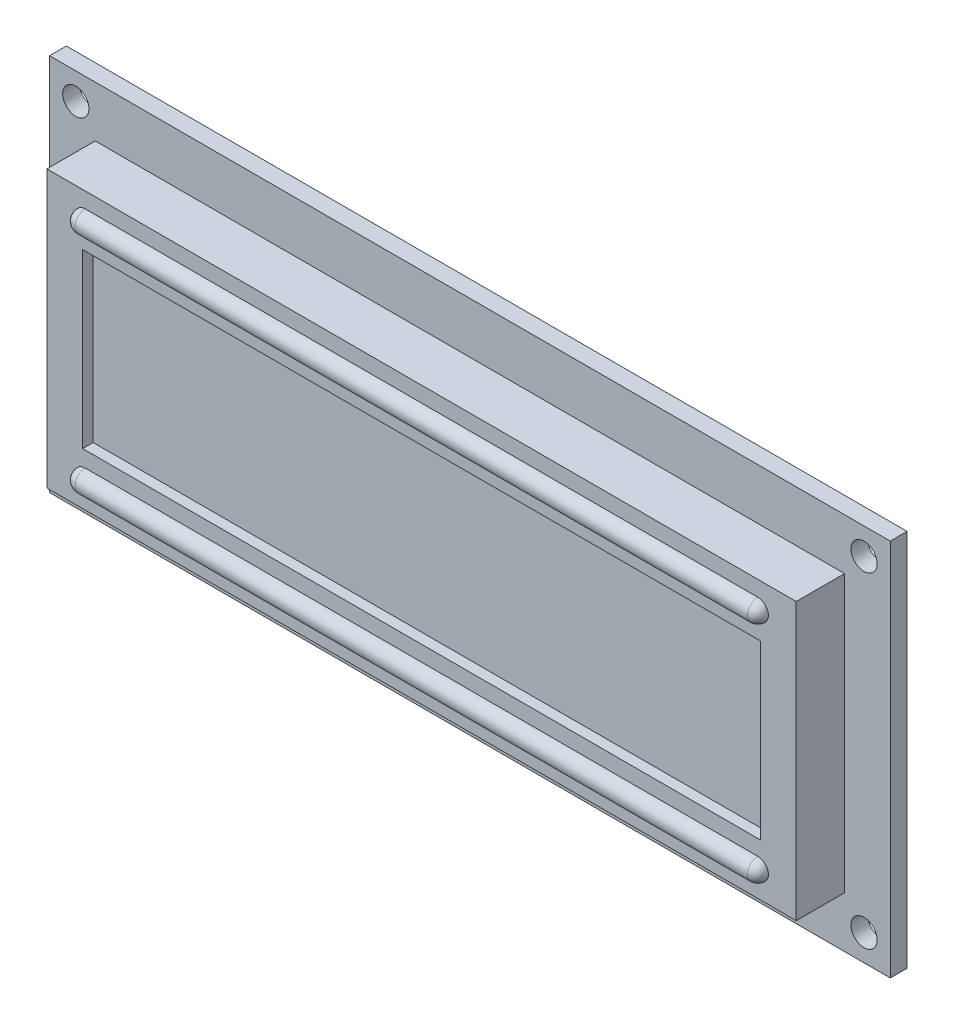
SolidWorks part; units mm, degrees
ref_plane "Alzado" through (0, 0, 0) normal (0, 0, 1) x (1, 0, 0)
ref_plane "Planta" through (0, 0, 0) normal (0, 1, 0) x (1, 0, 0)
ref_plane "Vista lateral" through (0, 0, 0) normal (1, 0, 0) x (0, 0, -1)
sketch "Croquis1" plane through (0, 0, 0) normal (0, 0, 1) x (1, 0, 0)
  line L0 (0, 18) -> (2.5, 18) construction
  line L1 (0, 0) -> (80, 0)
  line L2 (0, 0) -> (0, 36)
  line L3 (0, 36) -> (80, 36)
  line L4 (80, 0) -> (80, 36)
  line L5 (2.5, 18) -> (2.5, 33.5) construction
  line L6 (2.5, 18) -> (2.5, 2.5) construction
  line L7 (2.5, 2.5) -> (77.5, 2.5) construction
  line L8 (77.5, 2.5) -> (77.5, 33.5) construction
  line L9 (77.5, 33.5) -> (2.5, 33.5) construction
  circle A0 centre (77.5, 33.5) radius 1.25
  circle A1 centre (77.5, 2.5) radius 1.25
  circle A2 centre (2.5, 2.5) radius 1.25
  circle A3 centre (2.5, 33.5) radius 1.25
  dimension "D7" = 2.5
  dimension "D8" = 2.5
  dimension "D9" = 2.5
  dimension "D10" = 2.5
  dimension "D1" = 80
  dimension "D2" = 36
  dimension "D3" = 2.5
  dimension "D4" = 15.5
  dimension "D5" = 15.5
  dimension "D6" = 75
extrude "Saliente-Extruir2" add sketch "Croquis1" along normal blind 1.6
sketch "Croquis2" plane through (0, 0, 1.6) normal (0, 0, 1) x (1, 0, 0)
  line L0 (0, 18) -> (4.35, 18) construction
  line L1 (0, 36) -> (0, 0) construction
  line L2 (4.35, 18) -> (4.35, 31.15) construction
  line L3 (80, 0) -> (80, 36) construction
  line L4 (4.35, 31.15) -> (75.65, 31.15)
  line L5 (4.35, 31.15) -> (4.35, 4.85)
  line L6 (4.35, 4.85) -> (75.65, 4.85)
  line L7 (75.65, 31.15) -> (75.65, 4.85)
  line L8 (0, 0) -> (80, 0) construction
  line L9 (80, 36) -> (0, 36) construction
  line L10 (80, 0) -> (80, 36)
  line L11 (0, 0) -> (80, 0)
  line L12 (80, 36) -> (0, 36)
  line L13 (0, 36) -> (0, 0)
  dimension "D1" = 4.35
  dimension "D2" = 13.15
  dimension "D3" = 71.3
  dimension "D4" = 26.3
extrude "Saliente-Extruir3" add sketch "Croquis2" along normal blind 4.6 contours L7 L4 L5 L6
sketch "Croquis3" plane through (0, 0, 6.2) normal (0, 0, 1) x (1, 0, 0)
  line L0 (4.35, 31.15) -> (4.35, 4.85) construction
  line L1 (4.35, 31.15) -> (75.65, 31.15) construction
  line L2 (4.35, 4.85) -> (75.65, 4.85) construction
  line L3 (75.65, 31.15) -> (75.65, 4.85) construction
  line L4 (4.35, 31.15) -> (4.35, 4.85)
  line L5 (4.35, 31.15) -> (75.65, 31.15)
  line L6 (4.35, 4.85) -> (75.65, 4.85)
  line L7 (75.65, 31.15) -> (75.65, 4.85)
  line L8 (4.35, 18) -> (7.75, 18) construction
  line L9 (7.75, 18) -> (7.75, 26.2) construction
  line L11 (7.75, 26.2) -> (72.25, 26.2)
  line L12 (7.75, 26.2) -> (7.75, 9.8)
  line L13 (7.75, 9.8) -> (72.25, 9.8)
  line L14 (72.25, 26.2) -> (72.25, 9.8)
  dimension "D1" = 3.4
  dimension "D2" = 8.2
  dimension "D3" = 64.5
  dimension "D4" = 16.4
extrude "Cortar-Extruir1" cut sketch "Croquis3" against normal blind 1 contours L14 L11 L12 L13
sketch "Croquis4" plane through (0, 0, 6.2) normal (0, 0, 1) x (1, 0, 0)
  line L0 (4.35, 31.15) -> (75.65, 31.15) construction
  line L1 (7.75, 26.2) -> (72.25, 26.2) construction
  line L2 (7.75, 9.8) -> (72.25, 9.8) construction
  line L3 (4.35, 4.85) -> (75.65, 4.85) construction
  line L4 (4.35, 31.15) -> (75.65, 31.15)
  line L5 (7.75, 26.2) -> (72.25, 26.2)
  line L6 (7.75, 9.8) -> (72.25, 9.8)
  line L7 (4.35, 4.85) -> (75.65, 4.85)
  line L8 (40, 31.15) -> (40, 26.2) construction
  line L9 (40, 9.8) -> (40, 4.85) construction
  line L10 (40, 28.675) -> (72, 28.675)
  line L11 (40, 28.675) -> (8, 28.675)
  line L12 (7.75, 18) -> (72.25, 18) construction
  line L13 (7.75, 26.2) -> (7.75, 9.8) construction
  line L14 (72.25, 26.2) -> (72.25, 9.8) construction
  line L15 (40, 7.325) -> (72, 7.325)
  line L16 (40, 7.325) -> (8, 7.325)
  line L17 (72, 29.675) -> (72, 27.675)
  line L18 (72, 8.325) -> (72, 6.325) construction
  line L19 (8, 8.325) -> (8, 6.325) construction
  line L20 (8, 29.675) -> (8, 27.675) construction
  arc A0 (8, 29.675) -> (8, 27.675) centre (8, 28.675) ccw
  arc A1 (72, 27.675) -> (72, 29.675) centre (72, 28.675) ccw
  arc A2 (72, 8.325) -> (72, 6.325) centre (72, 7.325) cw
  arc A3 (8, 6.325) -> (8, 8.325) centre (8, 7.325) cw
  dimension "D3" = 2
  dimension "D4" = 2
  dimension "D1" = 32
  dimension "D2" = 32
ref_plane "Plano1" through (40, 0, 0) normal (1, 0, 0) x (0, 0, -1)
sketch "Croquis5" plane through (40, 0, 0) normal (1, 0, 0) x (0, 0, -1)
  line L0 (-6.2, 31.15) -> (-6.2, 26.2) construction
  circle A0 centre (-6.2, 28.675) radius 1
  circle A1 centre (-6.2, 7.325) radius 1
  dimension "D1" = 2
  dimension "D2" = 2
extrude "Saliente-Extruir4" add sketch "Croquis5" along normal mid plane 64
revolve "Revolución3" add sketch "Croquis4" angle 90 about L17
sketch "Croquis6" plane through (0, 0, 6.2) normal (0, 0, 1) x (1, 0, 0)
  line L0 (8, 29.675) -> (8, 27.675) construction
  line L1 (8, 29.675) -> (8, 27.675)
  arc A0 (8, 29.675) -> (8, 27.675) centre (8, 28.675) ccw construction
  arc A1 (8, 29.675) -> (8, 27.675) centre (8, 28.675) ccw
revolve "Revolución4" add sketch "Croquis6" angle 360 about L1
sketch "Croquis7" plane through (0, 0, 6.2) normal (0, 0, 1) x (1, 0, 0)
  line L0 (8, 8.325) -> (8, 6.325) construction
  line L1 (8, 8.325) -> (8, 6.325)
  arc A0 (8, 8.325) -> (8, 6.325) centre (8, 7.325) ccw construction
  arc A1 (8, 8.325) -> (8, 6.325) centre (8, 7.325) ccw
revolve "Revolución5" add sketch "Croquis7" angle 360 about L1
sketch "Croquis8" plane through (0, 0, 6.2) normal (0, 0, 1) x (1, 0, 0)
  line L0 (72, 8.325) -> (72, 6.325) construction
  line L1 (72, 8.325) -> (72, 6.325)
  arc A0 (72, 6.325) -> (72, 8.325) centre (72, 7.325) ccw construction
  arc A1 (72, 6.325) -> (72, 8.325) centre (72, 7.325) ccw
revolve "Revolución6" add sketch "Croquis8" angle 360 about L1
